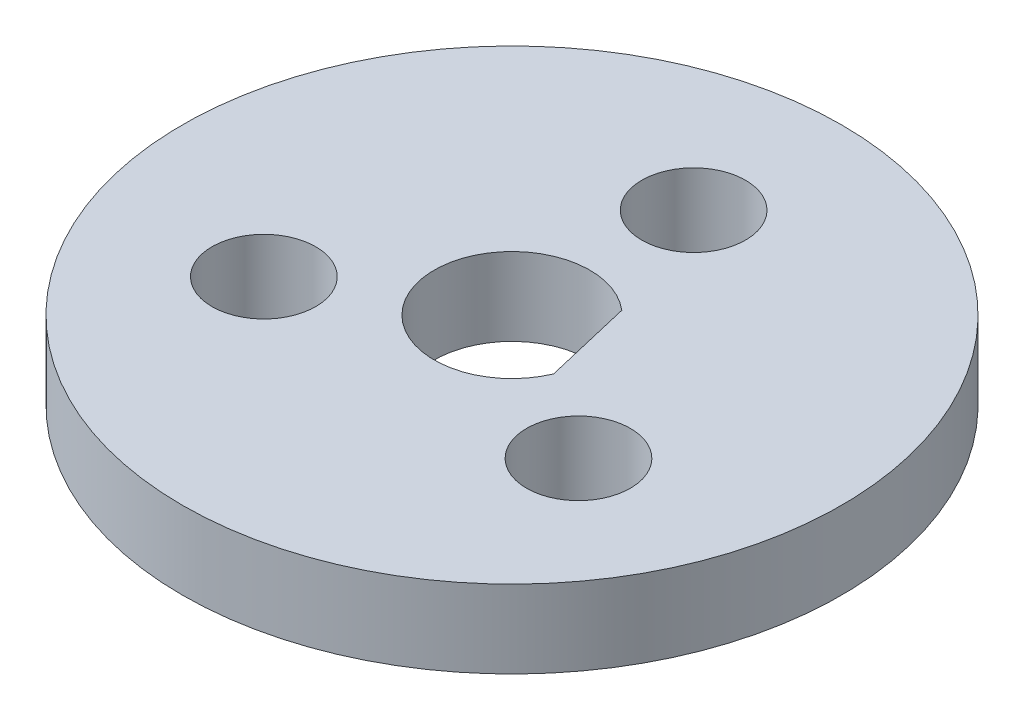
SolidWorks part; units mm, degrees
ref_plane "Front" through (0, 0, 0) normal (0, 0, 1) x (1, 0, 0)
ref_plane "Top" through (0, 0, 0) normal (0, 1, 0) x (1, 0, 0)
ref_plane "Right" through (0, 0, 0) normal (1, 0, 0) x (0, 0, -1)
sketch "Sketch1" plane through (0, 0, 0) normal (0, 1, 0) x (1, 0, 0)
  circle A0 centre (0, 0) radius 12.7
extrude "Boss-Extrude1" add sketch "Sketch1" along normal blind 3
sketch "Sketch2" plane through (0, 3, 0) normal (0, 1, 0) x (1, 0, 0)
  line L0 (1.9565, 2.2742) -> (2.7659, -1.1617)
  circle A0 centre (0, 0) radius 3
  dimension "D1" = 3.53
extrude "Cut-Extrude1" cut sketch "Sketch2" against normal blind 10 contours L0 A0
sketch "Sketch3" plane through (0, 3, 0) normal (0, 1, 0) x (1, 0, 0)
  circle A0 centre (0, 0) radius 7
  circle A1 centre (0, 7) radius 2
  circle A2 centre (6.0622, -3.5) radius 2
  circle A3 centre (-6.0622, -3.5) radius 2
  point P11 (0, 0)
  dimension "D1" = 3
extrude "Cut-Extrude2" cut sketch "Sketch3" against normal blind 5 contours A1 | A3 | A2
